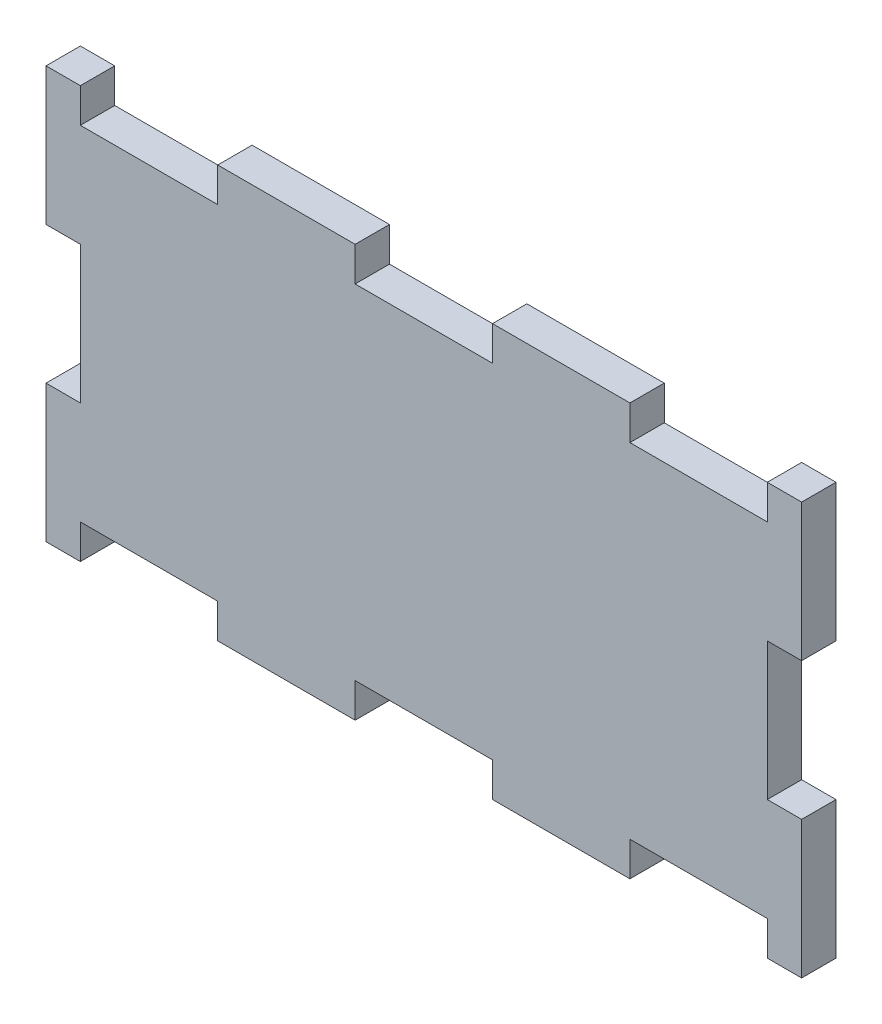
SolidWorks part; units mm, degrees
ref_plane "정면" through (0, 0, 0) normal (0, 0, 1) x (1, 0, 0)
ref_plane "윗면" through (0, 0, 0) normal (0, 1, 0) x (1, 0, 0)
ref_plane "우측면" through (0, 0, 0) normal (1, 0, 0) x (0, 0, -1)
sketch "스케치1" plane through (0, 0, 0) normal (0, 0, 1) x (1, 0, 0)
  line L1 (-50, 25) -> (50, 25)
  line L2 (-50, 25) -> (-50, -25)
  line L3 (-50, -25) -> (50, -25)
  line L4 (50, 25) -> (50, -25)
  line L5 (-50, 25) -> (50, -25) construction
  line L6 (-50, -25) -> (50, 25) construction
  point P0 (0, 0)
  dimension "D1" = 50
  dimension "D2" = 100
extrude "보스-돌출1" add sketch "스케치1" along normal blind 5
sketch "스케치2" plane through (0, 0, 5) normal (0, 0, 1) x (1, 0, 0)
  line L5 (28.2908, 0) -> (66.9345, 0) construction
  line L9 (50, -25) -> (50, 25) construction
  line L10 (50, -10) -> (55, -10)
  line L11 (50, -10) -> (50, -30)
  line L12 (50, -30) -> (55, -30)
  line L13 (55, -10) -> (55, -30)
  dimension "D1" = 10
  dimension "D2" = 20
  dimension "D3" = 5
extrude "보스-돌출2" add sketch "스케치2" against normal up to surface (5 mm away) up to face at (0, 0, 0)
mirror "대칭 복사1" about plane through (0, 0, 0) normal (1, 0, 0) of "보스-돌출2"
sketch "스케치3" plane through (0, 0, 5) normal (0, 0, 1) x (1, 0, 0)
  line L0 (0, 31.8109) -> (0, -7.2113) construction
  line L1 (50, 25) -> (-50, 25) construction
  line L2 (10, 25) -> (30, 25)
  line L3 (10, 25) -> (10, 30)
  line L4 (10, 30) -> (30, 30)
  line L5 (30, 25) -> (30, 30)
  dimension "D1" = 10
  dimension "D2" = 20
  dimension "D3" = 5
extrude "보스-돌출3" add sketch "스케치3" against normal up to surface (5 mm away) up to face at (0, -13.3333, 0)
mirror "대칭 복사2" about plane through (0, 0, 0) normal (1, 0, 0) of "보스-돌출3"
mirror "대칭 복사3" about plane through (0, 0, 0) normal (0, 1, 0) of "대칭 복사2", "보스-돌출3"
pattern_linear "선형 패턴2" count 2 spacing 40 along (0, 1, 0) of "대칭 복사1", "보스-돌출2"
